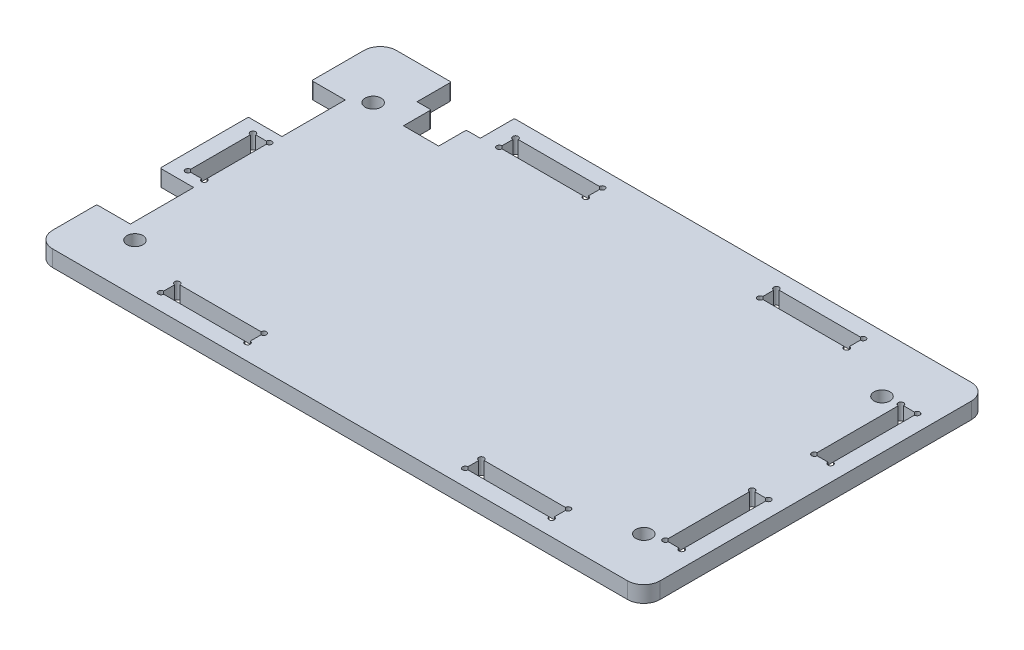
SolidWorks part; units mm, degrees
material "Acrylic (Medium-high impact)"
ref_plane "Front Plane" through (0, 0, 0) normal (0, 0, 1) x (1, 0, 0)
ref_plane "Top Plane" through (0, 0, 0) normal (0, 1, 0) x (1, 0, 0)
ref_plane "Right Plane" through (0, 0, 0) normal (1, 0, 0) x (0, 0, -1)
sketch "Sketch1" plane through (0, 0, 0) normal (0, 1, 0) x (1, 0, 0)
  line L0 (-50, 24.25) -> (50, 24.25) construction
  line L1 (-50, -25.75) -> (50, -25.75) construction
  line L2 (-50, -25.75) -> (-50, 25.75) construction
  line L3 (-50, 25.75) -> (50, 25.75) construction
  line L4 (50, -25.75) -> (50, 25.75) construction
  line L5 (-50, -25.75) -> (50, 25.75) construction
  line L6 (-50, 25.75) -> (50, -25.75) construction
  line L7 (-33.75, 25.45) -> (-31.41, 25.45)
  line L8 (-53.2, -31.75) -> (53, -31.75)
  line L9 (-56.2, -28.75) -> (-56.2, -20.85)
  line L10 (-53.2, 31.75) -> (-43.34, 31.75)
  line L11 (56, -28.75) -> (56, 28.75)
  line L12 (-43.09, 25.45) -> (-40.75, 25.45)
  line L13 (-43.09, 25.45) -> (-43.09, 31.5)
  line L14 (-52.7, -6.75) -> (-50.7, -6.75)
  line L15 (-31.41, 25.45) -> (-31.41, 31.5)
  line L16 (-50.2, -6.25) -> (-50.2, 4.75)
  line L17 (-52.7, 5.25) -> (-50.7, 5.25)
  line L18 (-40.5, 20.35) -> (-34, 20.35)
  line L19 (-40.5, 20.35) -> (-40.5, 25.2)
  line L20 (-53.2, -6.25) -> (-53.2, 4.75)
  line L21 (-34, 20.35) -> (-34, 25.2)
  line L22 (-56.2, -8.65) -> (-56.2, 7.15)
  line L23 (-55.95, 19.1) -> (-50, 19.1)
  line L25 (-31.16, 31.75) -> (53, 31.75)
  line L26 (-55.95, 7.4) -> (-50, 7.4)
  line L27 (-50, 19.1) -> (-50, 7.4)
  line L28 (-55.95, -8.9) -> (-50, -8.9)
  line L29 (-56.2, 19.35) -> (-56.2, 28.75)
  line L30 (-55.95, -20.6) -> (-50, -20.6)
  line L31 (-50, -8.9) -> (-50, -20.6)
  arc A0 (-53.2, 31.75) -> (-56.2, 28.75) centre (-53.2, 28.75) ccw
  arc A1 (-56.2, -28.75) -> (-53.2, -31.75) centre (-53.2, -28.75) ccw
  arc A2 (53, -31.75) -> (56, -28.75) centre (53, -28.75) ccw
  arc A3 (56, 28.75) -> (53, 31.75) centre (53, 28.75) ccw
  circle A4 centre (-47, 21.25) radius 1.4732
  circle A5 centre (-47, -22.75) radius 1.4732
  circle A6 centre (47, -22.75) radius 1.4732
  circle A7 centre (47, 21.25) radius 1.4732
  arc A8 (-53.2, -6.25) -> (-52.7, -6.75) centre (-53.2, -6.75) ccw
  arc A9 (-50.7, -6.75) -> (-50.2, -6.25) centre (-50.2, -6.75) ccw
  arc A10 (-52.7, 5.25) -> (-53.2, 4.75) centre (-53.2, 5.25) ccw
  arc A11 (-50.2, 4.75) -> (-50.7, 5.25) centre (-50.2, 5.25) ccw
  arc A12 (-55.95, 19.1) -> (-56.2, 19.35) centre (-55.95, 19.35) cw
  arc A13 (-56.2, 7.15) -> (-55.95, 7.4) centre (-55.95, 7.15) cw
  arc A14 (-55.95, -8.9) -> (-56.2, -8.65) centre (-55.95, -8.65) cw
  arc A15 (-56.2, -20.85) -> (-55.95, -20.6) centre (-55.95, -20.85) cw
  arc A16 (-40.5, 25.2) -> (-40.75, 25.45) centre (-40.75, 25.2) ccw
  arc A17 (-33.75, 25.45) -> (-34, 25.2) centre (-33.75, 25.2) ccw
  arc A18 (-31.16, 31.75) -> (-31.41, 31.5) centre (-31.16, 31.5) ccw
  arc A19 (-43.09, 31.5) -> (-43.34, 31.75) centre (-43.34, 31.5) ccw
  point P0 (0, 0)
  point P28 (-37.25, 28.6)
  point P33 (-37.25, 24.4)
  point P60 (-56.2, 19.1)
  point P65 (-56.2, -8.9)
  point P70 (-40.5, 25.45)
  point P73 (-34, 25.45)
  point P76 (-31.41, 31.75)
  point P79 (-43.09, 31.75)
  line B0 (-28.2, 28.25) -> (-28.2, 26.25)
  line B1 (-27.7, 25.75) -> (-12.7, 25.75)
  line B2 (-12.2, 28.25) -> (-12.2, 26.25)
  line B3 (-27.7, 28.75) -> (-12.7, 28.75)
  arc B4 (-27.7, 28.75) -> (-28.2, 28.25) centre (-28.2, 28.75) ccw
  arc B5 (-28.2, 26.25) -> (-27.7, 25.75) centre (-28.2, 25.75) ccw
  arc B6 (-12.2, 28.25) -> (-12.7, 28.75) centre (-12.2, 28.75) ccw
  arc B7 (-12.7, 25.75) -> (-12.2, 26.25) centre (-12.2, 25.75) ccw
  line B8 (20, 28.25) -> (20, 26.25)
  line B9 (20.5, 25.75) -> (35.5, 25.75)
  line B10 (36, 28.25) -> (36, 26.25)
  line B11 (20.5, 28.75) -> (35.5, 28.75)
  arc B12 (20.5, 28.75) -> (20, 28.25) centre (20, 28.75) ccw
  arc B13 (20, 26.25) -> (20.5, 25.75) centre (20, 25.75) ccw
  arc B14 (36, 28.25) -> (35.5, 28.75) centre (36, 28.75) ccw
  arc B15 (35.5, 25.75) -> (36, 26.25) centre (36, 25.75) ccw
  line B16 (-36.2, -26.25) -> (-36.2, -28.25)
  line B17 (-35.7, -28.75) -> (-20.7, -28.75)
  line B18 (-20.2, -26.25) -> (-20.2, -28.25)
  line B19 (-35.7, -25.75) -> (-20.7, -25.75)
  arc B20 (-35.7, -25.75) -> (-36.2, -26.25) centre (-36.2, -25.75) ccw
  arc B21 (-36.2, -28.25) -> (-35.7, -28.75) centre (-36.2, -28.75) ccw
  arc B22 (-20.2, -26.25) -> (-20.7, -25.75) centre (-20.2, -25.75) ccw
  arc B23 (-20.7, -28.75) -> (-20.2, -28.25) centre (-20.2, -28.75) ccw
  line B24 (20, -26.25) -> (20, -28.25)
  line B25 (20.5, -28.75) -> (35.5, -28.75)
  line B26 (36, -26.25) -> (36, -28.25)
  line B27 (20.5, -25.75) -> (35.5, -25.75)
  arc B28 (20.5, -25.75) -> (20, -26.25) centre (20, -25.75) ccw
  arc B29 (20, -28.25) -> (20.5, -28.75) centre (20, -28.75) ccw
  arc B30 (36, -26.25) -> (35.5, -25.75) centre (36, -25.75) ccw
  arc B31 (35.5, -28.75) -> (36, -28.25) centre (36, -28.75) ccw
  line B32 (50.5, -21.75) -> (52.5, -21.75)
  line B33 (53, -21.25) -> (53, -6.25)
  line B34 (50.5, -5.75) -> (52.5, -5.75)
  line B35 (50, -21.25) -> (50, -6.25)
  arc B36 (50, -21.25) -> (50.5, -21.75) centre (50, -21.75) ccw
  arc B37 (52.5, -21.75) -> (53, -21.25) centre (53, -21.75) ccw
  arc B38 (50.5, -5.75) -> (50, -6.25) centre (50, -5.75) ccw
  arc B39 (53, -6.25) -> (52.5, -5.75) centre (53, -5.75) ccw
  line B40 (50.5, 5.75) -> (52.5, 5.75)
  line B41 (53, 6.25) -> (53, 21.25)
  line B42 (50.5, 21.75) -> (52.5, 21.75)
  line B43 (50, 6.25) -> (50, 21.25)
  arc B44 (50, 6.25) -> (50.5, 5.75) centre (50, 5.75) ccw
  arc B45 (52.5, 5.75) -> (53, 6.25) centre (53, 5.75) ccw
  arc B46 (50.5, 21.75) -> (50, 21.25) centre (50, 21.75) ccw
  arc B47 (53, 21.25) -> (52.5, 21.75) centre (53, 21.75) ccw
  dimension "D8" = 3
  dimension "D10" = 6
  dimension "D13" = 6
  dimension "D16" = 6
  dimension "D19" = 6
  dimension "D22" = 2.9464
  dimension "D25" = 2.9464
  dimension "D28" = 2.9464
  dimension "D31" = 2.9464
  dimension "D34" = 3
  dimension "D35" = 20
  dimension "D36" = 20
  dimension "D37" = 3
  dimension "D44" = 10
  dimension "D45" = 3
  dimension "D46" = 3
  dimension "D47" = 10
  dimension "D60" = 2.59
  dimension "D61" = 5.84
  dimension "D62" = 0.5
  dimension "D63" = 0.5
  dimension "D75" = 2.15
  dimension "D76" = 0.25
  dimension "D77" = 0.25
  dimension "D32" = 3
  dimension "D33" = 28
  dimension "D41" = 0.5
  dimension "D42" = 0.5
  dimension "D52" = 0.5
  dimension "D53" = 0.5
  dimension "D1" = 100
  dimension "D2" = 51.5
  dimension "D3" = 50
  dimension "D4" = 6.2
  dimension "D5" = 6
  dimension "D6" = 6
  dimension "D7" = 6
  dimension "D9" = 3
  dimension "D11" = 3
  dimension "D12" = 3
  dimension "D14" = 3
  dimension "D15" = 3
  dimension "D17" = 3
  dimension "D18" = 3
  dimension "D20" = 3
  dimension "D21" = 3
  dimension "D23" = 3
  dimension "D24" = 3
  dimension "D26" = 3
  dimension "D27" = 3
  dimension "D29" = 3
  dimension "D30" = 3
  dimension "D38" = 20
  dimension "D39" = 3
  dimension "D40" = 26.5
  dimension "D43" = 3
  dimension "D48" = 57.5
  dimension "D49" = 23.5
  dimension "D50" = 25
  dimension "D51" = 106.2
  dimension "D54" = 12.75
  dimension "D55" = 11.68
  dimension "D56" = 6.3
  dimension "D57" = 5.1
  dimension "D58" = 6.5
  dimension "D59" = 0
  dimension "D64" = 2
  dimension "D65" = 2
  dimension "D66" = 3
  dimension "D67" = 12
  dimension "D68" = 12
  dimension "D69" = 3
  dimension "D70" = 3
  dimension "D71" = 0.5
  dimension "D72" = 11.7
  dimension "D73" = 2.15
  dimension "D74" = 11.7
sketch_block_instance "Block2-1"
sketch_block "Block2" parameters "D1"=0.5, "D2"=0.5, "D3"=0.5, "D4"=0.5, "D5"=15, "D6"=15, "D7"=2, "D8"=2, "D9"=3, "D10"=16, "D11"=16, "D12"=3, "D13"=0.5, "D14"=0.5
sketch_block_instance "Block2-2"
sketch_block_instance "Block2-3"
sketch_block_instance "Block2-4"
sketch_block_instance "Block2-7"
sketch_block_instance "Block2-8"
extrude "Boss-Extrude1" add sketch "Sketch1" along normal blind 3
